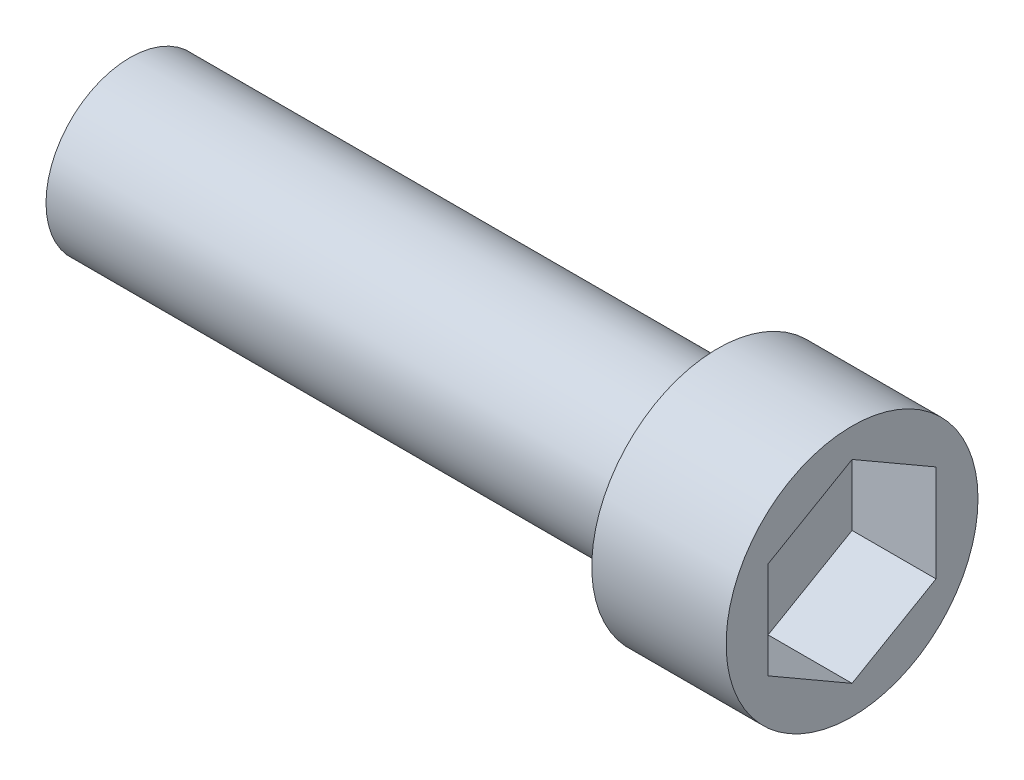
SolidWorks part; units mm, degrees
ref_plane "Front Plane" through (0, 0, 0) normal (0, 0, 1) x (1, 0, 0)
ref_plane "Top Plane" through (0, 0, 0) normal (0, 1, 0) x (1, 0, 0)
ref_plane "Right Plane" through (0, 0, 0) normal (1, 0, 0) x (0, 0, -1)
sketch "Sketch1" plane through (0, 0, 0) normal (1, 0, 0) x (0, 0, -1)
  circle A0 centre (0, 0) radius 7.5
extrude "Boss-Extrude1" add sketch "Sketch1" along normal blind 8 contours A0
sketch "Sketch2" plane through (8, 0, 0) normal (1, 0, 0) x (0, 0, -1)
  line L1 (0, -5.7735) -> (5, -2.8868)
  line L2 (5, -2.8868) -> (5, 2.8868)
  line L3 (5, 2.8868) -> (0, 5.7735)
  line L4 (0, 5.7735) -> (-5, 2.8868)
  line L5 (-5, 2.8868) -> (-5, -2.8868)
  line L6 (-5, -2.8868) -> (0, -5.7735)
extrude "Cut-Extrude1" cut sketch "Sketch2" against normal blind 5
sketch "Sketch3" plane through (0, 0, 0) normal (-1, 0, 0) x (0, 0, 1)
  circle A0 centre (0, 0) radius 5
extrude "Extrude-Thin1" add sketch "Sketch3" along normal blind 35 thin contours A0 thin type one direction reverse wall 1.69
